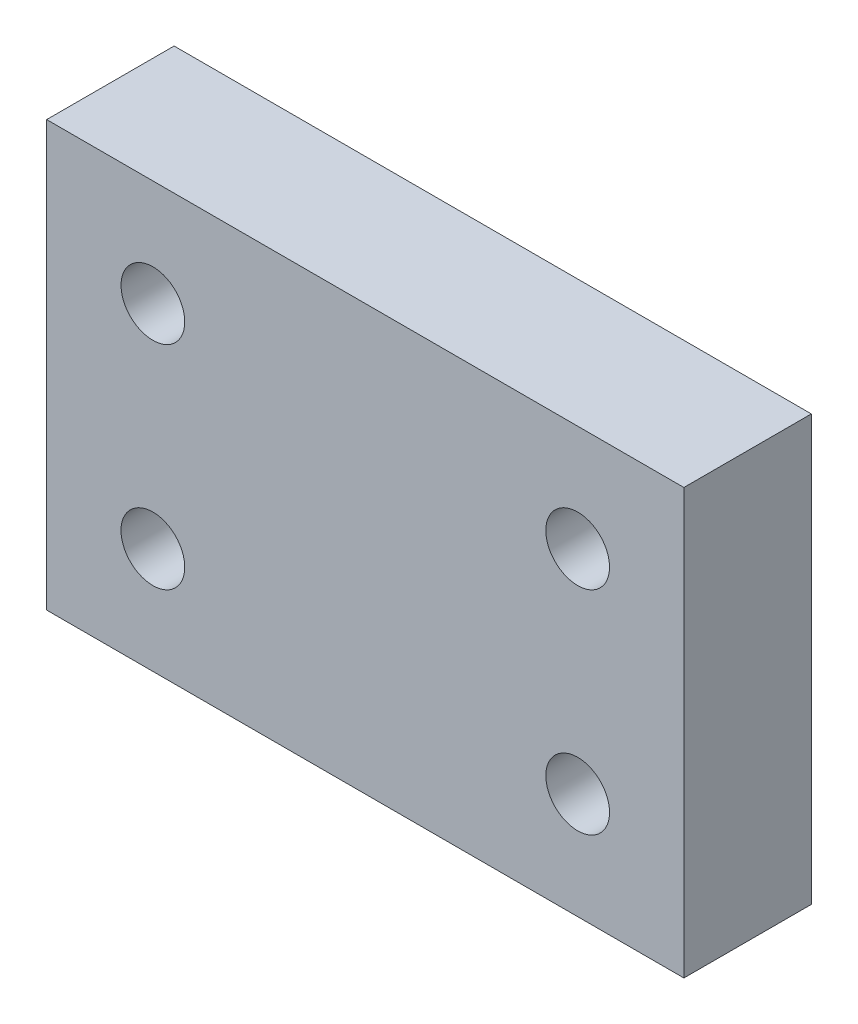
SolidWorks part; units mm, degrees
ref_plane "Plan de face" through (0, 0, 0) normal (0, 0, 1) x (1, 0, 0)
ref_plane "Plan de dessus" through (0, 0, 0) normal (0, 1, 0) x (1, 0, 0)
ref_plane "Plan de droite" through (0, 0, 0) normal (1, 0, 0) x (0, 0, -1)
sketch "Esquisse1" plane through (0, 0, 0) normal (0, 0, 1) x (1, 0, 0)
  line L0 (15, 20) -> (15, 0) construction
  line L1 (0, 0) -> (30, 0)
  line L2 (0, 0) -> (0, 20)
  line L3 (0, 20) -> (30, 20)
  line L4 (30, 0) -> (30, 20)
  line L5 (0, 10) -> (30, 10) construction
  circle A0 centre (5, 15) radius 1.5
  circle A1 centre (25, 15) radius 1.5
  circle A2 centre (25, 5) radius 1.5
  circle A3 centre (5, 5) radius 1.5
  point P13 (1.8374, 22.4689)
  dimension "D1" = 30
  dimension "D2" = 20
  dimension "D3" = 5
  dimension "D4" = 5
extrude "Boss.-Extru.1" add sketch "Esquisse1" along normal blind 6
